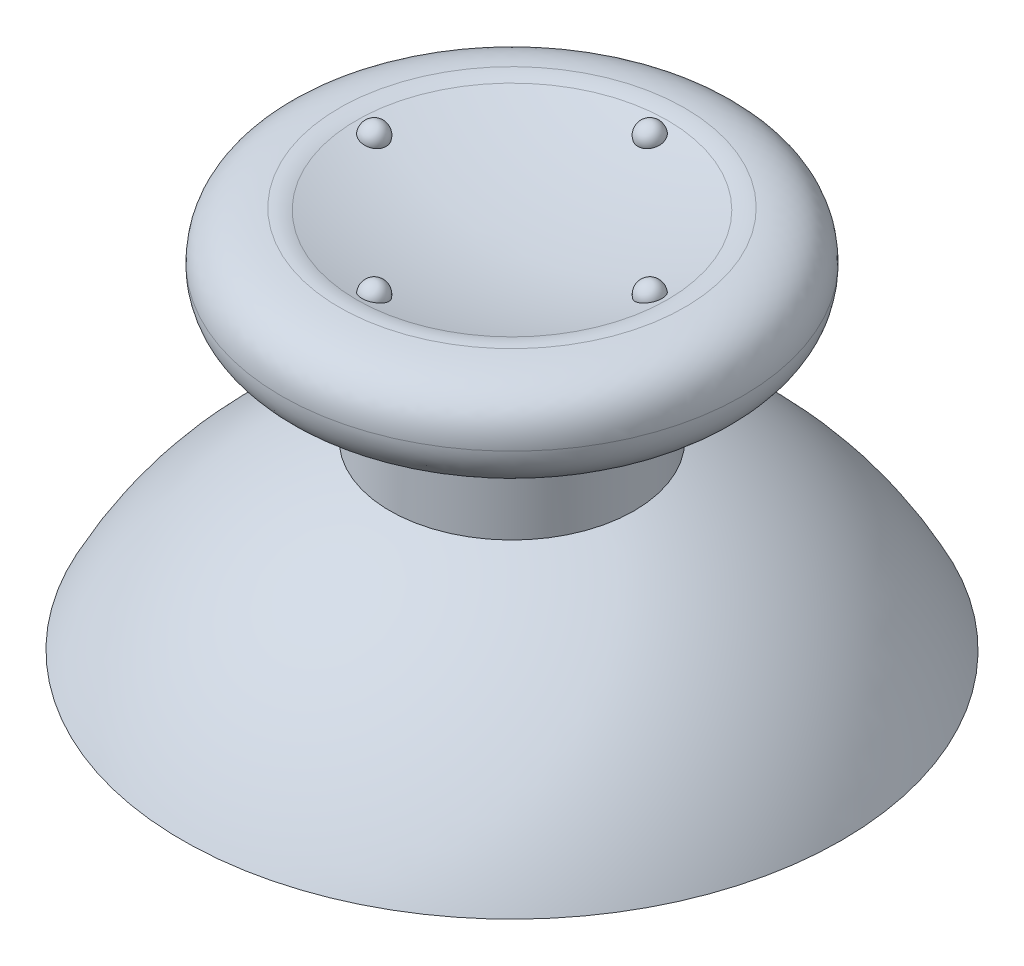
SolidWorks part; units mm, degrees
ref_plane "Front" through (0, 0, 0) normal (0, 0, 1) x (1, 0, 0)
ref_plane "Top" through (0, 0, 0) normal (0, 1, 0) x (1, 0, 0)
ref_plane "Right" through (0, 0, 0) normal (1, 0, 0) x (0, 0, -1)
sketch "Sketch1" plane through (0, 0, 0) normal (0, 0, 1) x (1, 0, 0)
  line L0 (14.465, 0) -> (-14.465, 0) construction
  line L1 (0, 4.8181) -> (0, 12.1229) construction
  line L2 (4.875, 11.15) -> (0, 11.15) construction
  line L3 (4.875, 7.25) -> (4.875, 11.15)
  line L4 (0, -8.5482) -> (0, 8.5482) construction
  line L5 (6.5, 15.3) -> (0, 15.3) construction
  line L6 (9.2, 13.3788) -> (9.2, 0) construction
  line L7 (8.2925, 14.0246) -> (8.2925, 12.9111) construction
  line L8 (3.625, 6.5927) -> (0, 6.5927)
  line L9 (0, 14.3) -> (0, 6.5927)
  line L10 (12.0183, 0) -> (13.15, 0)
  arc A0 (13.15, 0) -> (4.875, 7.25) centre (0, -6.6617) ccw
  arc A1 (0, 14.3) -> (6.5, 15.3) centre (0, 35.925) ccw
  arc A2 (12.0183, 0) -> (3.625, 6.5927) centre (0, -6.6617) ccw
  parabola Q0 (6.5, 15.3) -> (9.2, 13.3788) focus (8.2925, 14.0246) apex (8.8949, 14.4533)
  parabola Q1 (4.875, 11.15) -> (9.2, 13.3788) focus (8.2925, 12.9111) apex (9.0096, 12.5416)
  point P0 (9.2, 13.3788)
  point P6 (6.5, 15.3)
  dimension "D10" = 1
  dimension "D1" = 26.3
  dimension "D2" = 3.9
  dimension "D3" = 9.75
  dimension "D4" = 7.25
  dimension "D5" = 18.4
  dimension "D6" = 15.3
  dimension "D7" = 1
  dimension "D8" = 13
  dimension "D9" = 7.25
revolve "Revolve1" add sketch "Sketch1" angle 360 about L1
fillet "Fillet1" radius 2 1 edges at (0, 15.3, -6.5)
sketch "Sketch2" plane through (0, 0, 0) normal (0, 0, 1) x (1, 0, 0)
  line L1 (0, 1.8599) -> (0, 3.5133) construction
  line L3 (6.7756, 15.2925) -> (-6.7756, 15.2925) construction
  line L4 (5, 15.0425) -> (6, 15.0425)
  arc A0 (6, 15.0425) -> (5, 15.0425) centre (5.5, 15.0425) ccw
  arc A1 (5, 15.0425) -> (6, 15.0425) centre (5.5, 15.0425) ccw construction
  dimension "D1" = 11
  dimension "D2" = 1
  dimension "D3" = 0.25
revolve "Revolve2" add sketch "Sketch2" angle 360 about L4
pattern_circular "CirPattern1" count 4 over 360 about axis through (0, 0, 0) along (0, 1, 0) of "Revolve2"
sketch "Sketch7" plane through (0, 6.5927, 0) normal (0, -1, 0) x (1, 0, 0)
  circle A0 centre (0, 0) radius 2.75
  dimension "D1" = 5.5
extrude "Extrude4" add sketch "Sketch7" along normal offset from surface (5.5927 mm away) 1 up to face at (0, 0, -13.15)
chamfer "Chamfer7" distance 0.5 angle 30 1 edges at (0, 1, -2.75)
ref_plane "Plane1" through (0, 0, 0) normal (-0.7071, 0, 0.7071) x (0.7071, 0, 0.7071)
sketch "Sketch4" plane through (0, 0, 0) normal (0.7071, 0, -0.7071) x (-0.7071, 0, -0.7071)
  line L0 (-5.5, 5.9307) -> (-5.5, 2.4886)
  line L1 (-5.5, 2.4886) -> (-2.3791, 1)
  line L2 (-2.3791, 1) -> (2.3791, 1)
  line L4 (0, 4.0833) -> (0, 5.9358) construction
  line L5 (5.5, 5.9307) -> (5.5, 2.4886)
  line L6 (5.5, 2.4886) -> (2.3791, 1)
  line L7 (-13.15, 0) -> (13.15, 0) construction
  line L8 (-3.625, 6.5927) -> (3.625, 6.5927) construction
  line L9 (-3.625, 6.5927) -> (3.625, 6.5927)
  arc A0 (-3.625, 6.5927) -> (-12.0183, 0) centre (0, -6.6617) ccw construction
  arc A1 (12.0183, 0) -> (3.625, 6.5927) centre (0, -6.6617) ccw construction
  arc A2 (5.5, 5.9307) -> (3.625, 6.5927) centre (0, -6.6617) ccw
  arc A3 (-3.625, 6.5927) -> (-5.5, 5.9307) centre (0, -6.6617) ccw
  point P15 (0, 1)
  point P17 (8.6687, 4)
  dimension "D1" = 11
  dimension "D2" = 1
  dimension "D3" = 4
  dimension "D4" = 25.5
extrude "Extrude1" add sketch "Sketch4" along normal mid plane 2
sketch "Sketch5" plane through (0, 0, 0) normal (-0.7071, 0, 0.7071) x (0.7071, 0, 0.7071)
  line L0 (-5.5, 2.4886) -> (-8.6687, 4)
  line L5 (-2.3791, 1) -> (-5.5, 2.4886) construction
  line L6 (5.5, 2.4886) -> (8.6687, 4)
  line L7 (5.5, 2.4886) -> (2.3791, 1) construction
  line L9 (5.5, 2.4886) -> (5.5, 5.9307)
  line L10 (-5.5, 2.4886) -> (-5.5, 5.9307)
  arc A2 (-5.5, 5.9307) -> (-12.0183, 0) centre (0, -6.6617) ccw construction
  arc A3 (12.0183, 0) -> (5.5, 5.9307) centre (0, -6.6617) ccw construction
  arc A4 (-5.5, 5.9307) -> (-8.6687, 4) centre (0, -6.6617) ccw
  arc A5 (8.6687, 4) -> (5.5, 5.9307) centre (0, -6.6617) ccw
extrude "Extrude2" add sketch "Sketch5" along normal mid plane 0.75
pattern_circular "CirPattern2" count 2 every 90 about axis through (0, 0, 0) along (0, 1, 0) of "Extrude1", "Extrude2"
chamfer "Chamfer8" distance 0.3 4 edges at (-1.6823, 1, 1.6823) (1.6823, 1, -1.6823) (1.6823, 1, 1.6823) (-1.6823, 1, -1.6823)
sketch "Sketch9" plane through (0, 1, 0) normal (0, -1, 0) x (1, 0, 0)
  line L0 (-1.4524, 1.375) -> (-0.375, 1.375)
  line L1 (0.2829, 0) -> (1.2229, 0) construction
  line L2 (-1.4524, -1.375) -> (1.4524, -1.375)
  line L3 (0, -8.5482) -> (0, 8.5482) construction
  line L4 (0.375, 1.375) -> (1.4524, 1.375)
  arc A0 (-1.4524, 1.375) -> (-1.4524, -1.375) centre (0, 0) ccw
  arc A1 (1.4524, -1.375) -> (1.4524, 1.375) centre (0, 0) ccw
  arc A2 (-0.375, 1.375) -> (0.375, 1.375) centre (0, 1.0443) cw
  dimension "D1" = 4
  dimension "D3" = 0.5
  dimension "D4" = 0.75
  dimension "D2" = 2.75
extrude "Extrude5" cut sketch "Sketch9" against normal blind 4.5
sketch "Sketch10" plane through (0, 5.5, 0) normal (0, -1, 0) x (1, 0, 0)
  circle A0 centre (0, 0) radius 0.75
  dimension "D1" = 1.5
extrude "Extrude6" cut sketch "Sketch10" against normal blind 1.5
sketch "Pivot Point" plane through (0, 0, 0) normal (0, 0, 1) x (1, 0, 0)
  line L0 (0, -8.5482) -> (0, 8.5482) construction
  line L1 (14.465, 0) -> (-14.465, 0) construction
  line L2 (0, -5.75) -> (0, 5.5)
  line L3 (-0.375, 5.5) -> (0.375, 5.5) construction
  point P0 (0, -5.75)
  dimension "D1" = 5.75
